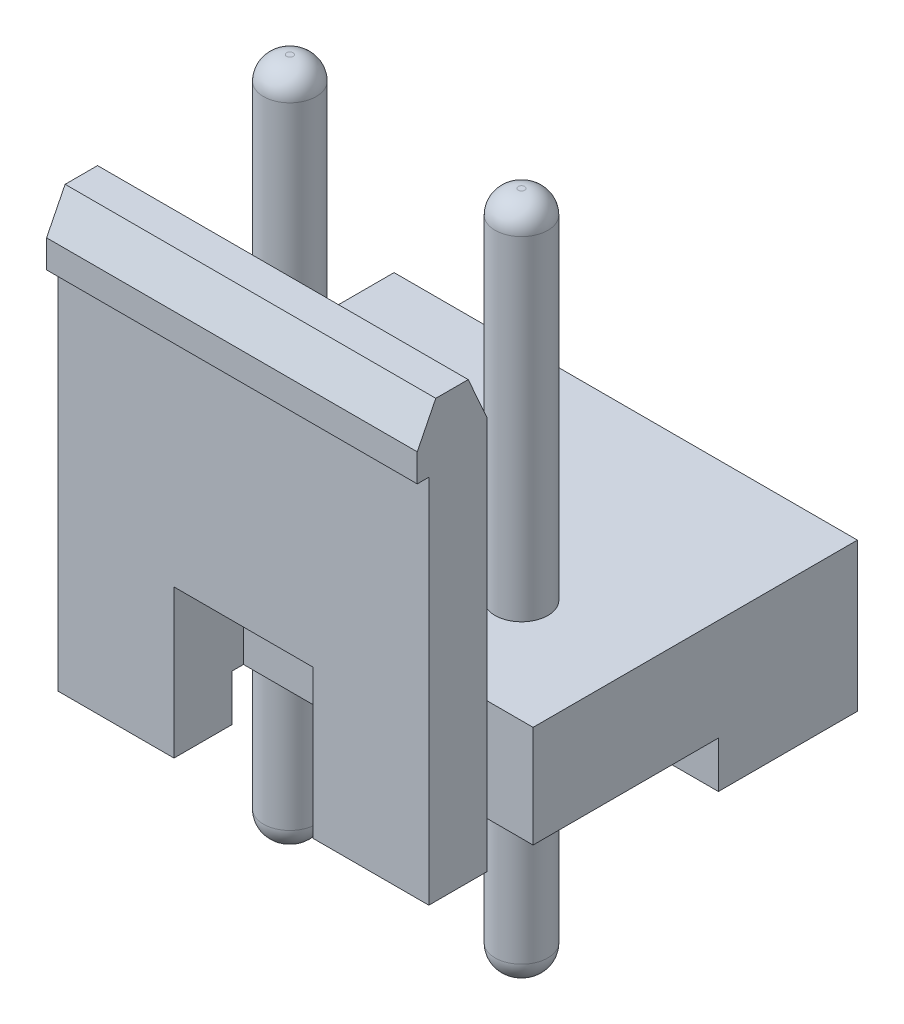
SolidWorks part; units mm, degrees
ref_plane "Alzado" through (0, 0, 0) normal (0, 0, 1) x (1, 0, 0)
ref_plane "Planta" through (0, 0, 0) normal (0, 1, 0) x (1, 0, 0)
ref_plane "Vista lateral" through (0, 0, 0) normal (1, 0, 0) x (0, 0, -1)
sketch "Croquis1" plane through (0, 0, 0) normal (0, 1, 0) x (1, 0, 0)
  line L1 (5, -4.25) -> (-5, -4.25)
  line L2 (5, -4.25) -> (5, 4.25)
  line L3 (5, 4.25) -> (-5, 4.25)
  line L4 (-5, -4.25) -> (-5, 4.25)
  line L5 (5, -4.25) -> (-5, 4.25) construction
  line L6 (5, 4.25) -> (-5, -4.25) construction
  point P0 (0, 0)
  dimension "D1" = 10
  dimension "D2" = 8.5
extrude "Saliente-Extruir1" add sketch "Croquis1" along normal blind 9.4
sketch "Croquis2" plane through (0, 9.4, 0) normal (0, 1, 0) x (1, 0, 0)
  line L0 (5, -4.25) -> (5, 4.25) construction
  line L1 (-5, 4.25) -> (5, 4.25)
  line L2 (-5, 4.25) -> (-5, -2.75)
  line L3 (-5, -2.75) -> (5, -2.75)
  line L4 (5, 4.25) -> (5, -2.75)
  line L5 (-5, -4.25) -> (5, -4.25) construction
  dimension "D1" = 1.5
extrude "Cortar-Extruir1" cut sketch "Croquis2" against normal blind 6.2
sketch "Croquis3" plane through (-5, 0, 0) normal (-1, 0, 0) x (0, 0, 1)
  line L1 (4.25, 0) -> (4, 0)
  line L2 (4.25, 0) -> (4.25, 8)
  line L3 (4.25, 8) -> (4, 8)
  line L4 (4, 0) -> (4, 8)
  dimension "D1" = 0.25
  dimension "D2" = 8
extrude "Cortar-Extruir2" cut sketch "Croquis3" against normal blind 10
sketch "Croquis4" plane through (0, 0, -4.25) normal (0, 0, -1) x (-1, 0, 0)
  line L0 (-5, 0) -> (5, 0) construction
  line L2 (-1.5, 0) -> (-1.5, 0.5)
  line L3 (-1.5, 0.5) -> (1.5, 0.5)
  line L4 (1.5, 0) -> (1.5, 0.5)
  line L5 (-1.5, -0.5) -> (1.5, 0.5) construction
  line L6 (-1.5, 0.5) -> (1.5, -0.5) construction
  line L7 (-1.5, 0) -> (1.5, 0)
  point P0 (0, 0)
  point P1 (0, 0)
  dimension "D1" = 1
  dimension "D2" = 3
extrude "Cortar-Extruir3" cut sketch "Croquis4" against normal blind 10
sketch "Croquis5" plane through (-5, 0, 0) normal (-1, 0, 0) x (0, 0, 1)
  line L0 (-4.25, 0) -> (4, 0) construction
  line L1 (2.75, 0) -> (-1.25, 0)
  line L2 (2.75, 0) -> (2.75, 1)
  line L3 (2.75, 1) -> (-1.25, 1)
  line L4 (-1.25, 0) -> (-1.25, 1)
  line L5 (2.75, 3.2) -> (2.75, 9.4) construction
  dimension "D1" = 4
  dimension "D2" = 1
extrude "Cortar-Extruir4" cut sketch "Croquis5" against normal blind 10
ref_plane "Plano1" through (0, 3.6, 0) normal (0, 1, 0) x (1, 0, 0)
sketch "Croquis6" plane through (0, 3.6, 0) normal (0, 1, 0) x (1, 0, 0)
  line L0 (-5, 4.25) -> (-5, -4.25) construction
  line L3 (-2.5, -0.5) -> (2.5, -0.5) construction
  circle A0 centre (-2.5, -0.5) radius 0.57
  circle A1 centre (2.5, -0.5) radius 0.57
  point P7 (0, 0)
  point P11 (0, 0)
  point P12 (0, 0)
  dimension "D2" = 1.14
  dimension "D1" = 5
  dimension "D3" = 0.5
extrude "Saliente-Extruir2" add sketch "Croquis6" along normal mid plane 14.6
fillet "Redondeo2" radius 0.5 4 edges at (-2.5, -3.7, 1.07) (-2.5, 10.9, 1.07) (2.5, 10.9, 1.07) (2.5, -3.7, 1.07)
sketch "Croquis7" plane through (0, 9.4, 0) normal (0, 1, 0) x (1, 0, 0)
  line L0 (-5, -2.75) -> (5, -2.75) construction
  line L1 (-5, -4.25) -> (-4, -4.25)
  line L2 (-5, -4.25) -> (-5, -2.75)
  line L3 (-5, -2.75) -> (-4, -2.75)
  line L4 (-4, -4.25) -> (-4, -2.75)
  line L5 (-5, -2.75) -> (5, -2.75) construction
  line L6 (5, -4.25) -> (4, -4.25)
  line L7 (5, -4.25) -> (5, -2.75)
  line L8 (5, -2.75) -> (4, -2.75)
  line L9 (4, -4.25) -> (4, -2.75)
  dimension "D1" = 1
extrude "Cortar-Extruir5" cut sketch "Croquis7" against normal blind 14.8
sketch "Croquis8" plane through (0, 0, 4) normal (0, 0, 1) x (1, 0, 0)
  line L1 (-1.5, 0) -> (1.5, 0)
  line L2 (-1.5, 0) -> (-1.5, 3.2)
  line L3 (-1.5, 3.2) -> (1.5, 3.2)
  line L4 (1.5, 0) -> (1.5, 3.2)
  dimension "D1" = 3
  dimension "D2" = 3.2
extrude "Cortar-Extruir6" cut sketch "Croquis8" against normal blind 1.5
sketch "Croquis9" plane through (-4, 0, 0) normal (-1, 0, 0) x (0, 0, 1)
  line L0 (4.25, 8.6) -> (4.25, 9.4)
  line L1 (4.25, 8) -> (4.25, 9.4) construction
  line L2 (4.25, 9.4) -> (3.85, 9.4)
  line L3 (4.25, 9.4) -> (2.75, 9.4) construction
  line L4 (3.85, 9.4) -> (4.25, 8.6)
  line L5 (2.75, 8.5) -> (2.75, 9.4)
  line L6 (2.75, 3.2) -> (2.75, 9.4) construction
  line L7 (2.75, 9.4) -> (3.15, 9.4)
  line L8 (3.15, 9.4) -> (2.75, 8.5)
  dimension "D1" = 0.8
  dimension "D2" = 0.9
  dimension "D3" = 0.4
  dimension "D4" = 0.4
extrude "Cortar-Extruir7" cut sketch "Croquis9" against normal blind 10
